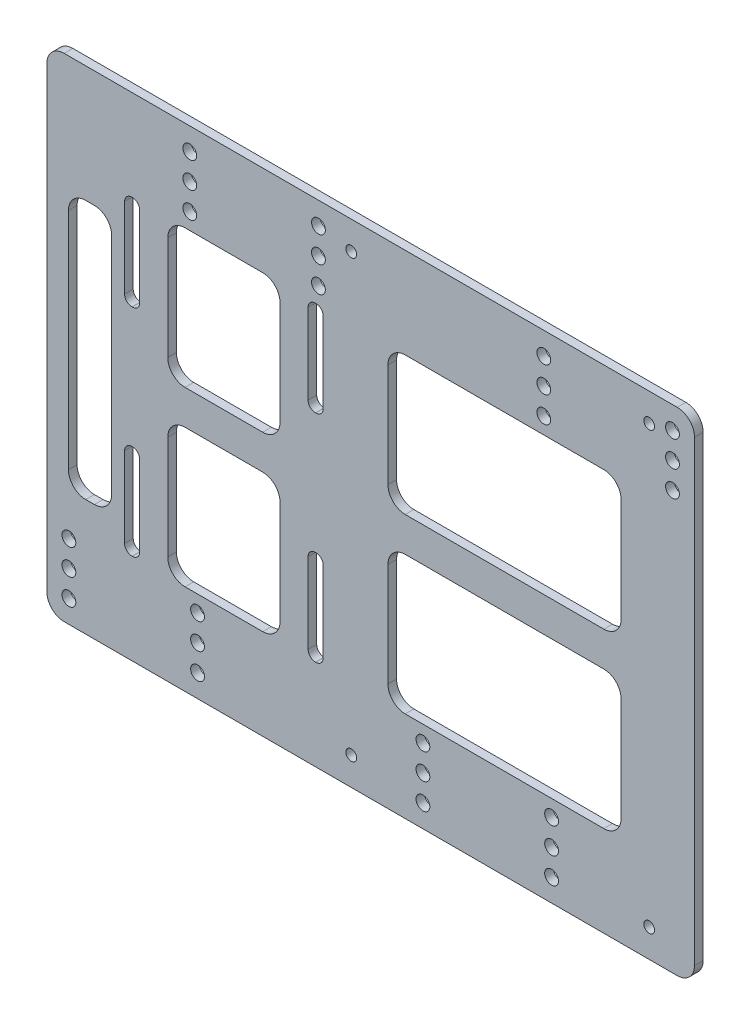
SolidWorks part; units mm, degrees
material "6061 Alloy"
ref_plane "Front Plane" through (0, 0, 0) normal (1, 0, 0) x (0, 1, 0)
ref_plane "Top Plane" through (0, 0, 0) normal (0, 0, 1) x (0, 1, 0)
ref_plane "Right Plane" through (0, 0, 0) normal (0, 1, 0) x (-1, 0, 0)
sketch "Sketch1" plane through (0, 0, 0) normal (0, 0, 1) x (0, 1, 0)
  line L0 (-53, -75) -> (53, -75)
  line L1 (57, -71) -> (57, 71)
  line L2 (53, 75) -> (-53, 75)
  line L3 (-57, 71) -> (-57, -71)
  arc A0 (53, -75) -> (57, -71) centre (53, -71) ccw
  arc A1 (57, 71) -> (53, 75) centre (53, 71) ccw
  arc A2 (-53, 75) -> (-57, 71) centre (-53, 71) ccw
  arc A3 (-57, -71) -> (-53, -75) centre (-53, -71) ccw
extrude "Boss-Extrude1" add sketch "Sketch1" along normal blind 2
sketch "Sketch2" plane through (0, 0, 0) normal (0, 0, 1) x (0, 1, 0)
  line L0 (-34.3, 11) -> (-15.7, 11)
  line L1 (-14, 12.7) -> (-14, 12.8)
  line L2 (-15.7, 14.5) -> (-34.3, 14.5)
  line L3 (-36, 12.8) -> (-36, 12.7)
  line L4 (-34.3, 53.5) -> (-15.7, 53.5)
  line L5 (-14, 55.2) -> (-14, 55.3)
  line L6 (-15.7, 57) -> (-34.3, 57)
  line L7 (-36, 55.3) -> (-36, 55.2)
  line L8 (15.7, 11) -> (34.3, 11)
  line L9 (36, 12.7) -> (36, 12.8)
  line L10 (34.3, 14.5) -> (15.7, 14.5)
  line L11 (14, 12.8) -> (14, 12.7)
  line L12 (15.7, 53.5) -> (34.3, 53.5)
  line L13 (36, 55.2) -> (36, 55.3)
  line L14 (34.3, 57) -> (15.7, 57)
  line L15 (14, 55.3) -> (14, 55.2)
  line L16 (-32, -58) -> (-8, -58)
  line L17 (-4, -54) -> (-4, -8)
  line L18 (-8, -4) -> (-32, -4)
  line L19 (-36, -8) -> (-36, -54)
  line L20 (-32, 21) -> (-8, 21)
  line L21 (-4, 25) -> (-4, 43)
  line L22 (-8, 47) -> (-32, 47)
  line L23 (-36, 43) -> (-36, 25)
  line L24 (8, -58) -> (32, -58)
  line L25 (36, -54) -> (36, -8)
  line L26 (32, -4) -> (8, -4)
  line L27 (4, -8) -> (4, -54)
  line L28 (8, 21) -> (32, 21)
  line L29 (36, 25) -> (36, 43)
  line L30 (32, 47) -> (8, 47)
  line L31 (4, 43) -> (4, 25)
  line L32 (-26, 60) -> (26, 60)
  line L33 (30, 64) -> (30, 66)
  line L34 (26, 70) -> (-26, 70)
  line L35 (-30, 66) -> (-30, 64)
  circle A0 centre (-51.8, 40.1) radius 1.6
  circle A1 centre (-51.8, 69.9) radius 1.6
  circle A2 centre (-45.8, 40.1) radius 1.6
  circle A3 centre (-45.8, 69.9) radius 1.6
  circle A4 centre (-39.8, 40.1) radius 1.6
  circle A5 centre (-39.8, 69.9) radius 1.6
  circle A6 centre (-51.8, -41.9) radius 1.6
  circle A7 centre (-51.8, -12.1) radius 1.6
  circle A8 centre (-45.8, -41.9) radius 1.6
  circle A9 centre (-45.8, -12.1) radius 1.6
  circle A10 centre (-39.8, -41.9) radius 1.6
  circle A11 centre (-39.8, -12.1) radius 1.6
  circle A12 centre (51.8, 12.1) radius 1.6
  circle A13 centre (51.8, 41.9) radius 1.6
  circle A14 centre (45.8, 12.1) radius 1.6
  circle A15 centre (45.8, 41.9) radius 1.6
  circle A16 centre (39.8, 12.1) radius 1.6
  circle A17 centre (39.8, 41.9) radius 1.6
  circle A18 centre (51.8, -69.9) radius 1.6
  circle A19 centre (51.8, -40.1) radius 1.6
  circle A20 centre (45.8, -69.9) radius 1.6
  circle A21 centre (45.8, -40.1) radius 1.6
  circle A22 centre (39.8, -69.9) radius 1.6
  circle A23 centre (39.8, -40.1) radius 1.6
  circle A24 centre (-50.5, -64.5) radius 1.25
  circle A25 centre (-50.5, 4.5) radius 1.25
  circle A26 centre (50.5, -64.5) radius 1.25
  circle A27 centre (50.5, 4.5) radius 1.25
  arc A28 (-15.7, 11) -> (-14, 12.7) centre (-15.7, 12.7) ccw
  arc A29 (-14, 12.8) -> (-15.7, 14.5) centre (-15.7, 12.8) ccw
  arc A30 (-34.3, 14.5) -> (-36, 12.8) centre (-34.3, 12.8) ccw
  arc A31 (-36, 12.7) -> (-34.3, 11) centre (-34.3, 12.7) ccw
  arc A32 (-15.7, 53.5) -> (-14, 55.2) centre (-15.7, 55.2) ccw
  arc A33 (-14, 55.3) -> (-15.7, 57) centre (-15.7, 55.3) ccw
  arc A34 (-34.3, 57) -> (-36, 55.3) centre (-34.3, 55.3) ccw
  arc A35 (-36, 55.2) -> (-34.3, 53.5) centre (-34.3, 55.2) ccw
  arc A36 (34.3, 11) -> (36, 12.7) centre (34.3, 12.7) ccw
  arc A37 (36, 12.8) -> (34.3, 14.5) centre (34.3, 12.8) ccw
  arc A38 (15.7, 14.5) -> (14, 12.8) centre (15.7, 12.8) ccw
  arc A39 (14, 12.7) -> (15.7, 11) centre (15.7, 12.7) ccw
  arc A40 (34.3, 53.5) -> (36, 55.2) centre (34.3, 55.2) ccw
  arc A41 (36, 55.3) -> (34.3, 57) centre (34.3, 55.3) ccw
  arc A42 (15.7, 57) -> (14, 55.3) centre (15.7, 55.3) ccw
  arc A43 (14, 55.2) -> (15.7, 53.5) centre (15.7, 55.2) ccw
  arc A44 (-8, -58) -> (-4, -54) centre (-8, -54) ccw
  arc A45 (-4, -8) -> (-8, -4) centre (-8, -8) ccw
  arc A46 (-32, -4) -> (-36, -8) centre (-32, -8) ccw
  arc A47 (-36, -54) -> (-32, -58) centre (-32, -54) ccw
  arc A48 (-8, 21) -> (-4, 25) centre (-8, 25) ccw
  arc A49 (-4, 43) -> (-8, 47) centre (-8, 43) ccw
  arc A50 (-32, 47) -> (-36, 43) centre (-32, 43) ccw
  arc A51 (-36, 25) -> (-32, 21) centre (-32, 25) ccw
  arc A52 (32, -58) -> (36, -54) centre (32, -54) ccw
  arc A53 (36, -8) -> (32, -4) centre (32, -8) ccw
  arc A54 (8, -4) -> (4, -8) centre (8, -8) ccw
  arc A55 (4, -54) -> (8, -58) centre (8, -54) ccw
  arc A56 (32, 21) -> (36, 25) centre (32, 25) ccw
  arc A57 (36, 43) -> (32, 47) centre (32, 43) ccw
  arc A58 (8, 47) -> (4, 43) centre (8, 43) ccw
  arc A59 (4, 25) -> (8, 21) centre (8, 25) ccw
  arc A60 (26, 60) -> (30, 64) centre (26, 64) ccw
  arc A61 (30, 66) -> (26, 70) centre (26, 66) ccw
  arc A62 (-26, 70) -> (-30, 66) centre (-26, 66) ccw
  arc A63 (-30, 64) -> (-26, 60) centre (-26, 64) ccw
extrude "Cut-Extrude6" cut sketch "Sketch2" against normal through all and the other way through all
